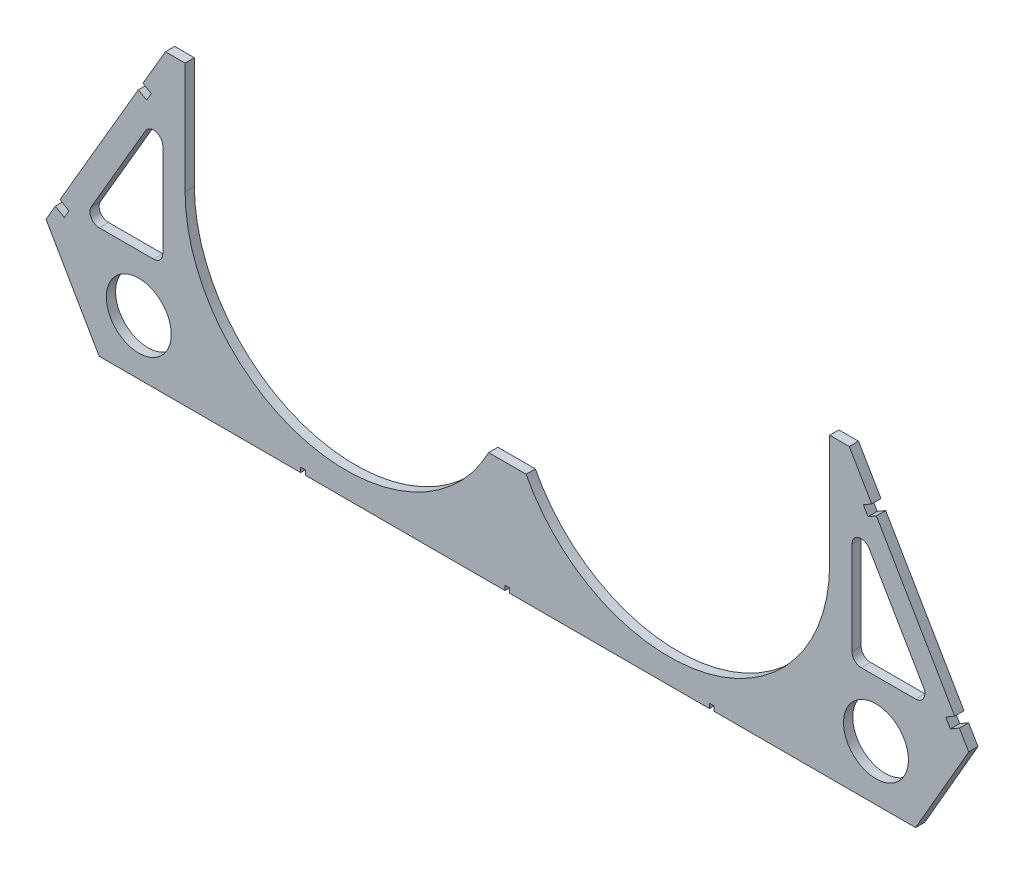
SolidWorks part; units mm, degrees
material "Balsa"
ref_plane "Front Plane" through (0, 0, 0) normal (0, 0, 1) x (1, 0, 0)
ref_plane "Top Plane" through (0, 0, 0) normal (0, 1, 0) x (1, 0, 0)
ref_plane "Right Plane" through (0, 0, 0) normal (1, 0, 0) x (0, 0, -1)
sketch "Sketch1" plane through (0, 0, 0) normal (0, 0, 1) x (1, 0, 0)
  line L1 (279.4, 0) -> (315.7855, 63.0215)
  line L3 (0, 0) -> (0, 203.2) construction
  line L5 (-234.0358, 203.2) -> (-315.7855, 63.0215)
  line L11 (279.4, 0) -> (-279.4, 0)
  line L14 (-234.0358, 203.2) -> (234.0358, 203.2)
  line L15 (234.0358, 203.2) -> (315.7855, 63.0215)
  line L16 (0, -796.8) -> (0, 49203.2) construction
  line L17 (-279.4, 0) -> (-315.7855, 63.0215)
  point P6 (114.3, 190.1315)
  point P12 (-114.3, 190.1315)
  dimension "D1" = 279.4
  dimension "D2" = 72.771
  dimension "D3" = 59.75
  dimension "D4" = 203.2
  dimension "D5" = 120
extrude "Boss-Extrude1" add sketch "Sketch1" along normal blind 6.35
sketch "Sketch4" plane through (0, 0, 6.35) normal (0, 0, 1) x (1, 0, 0)
  line L1 (-279.4, 0) -> (279.4, 0) construction
  line L3 (0, 203.2) -> (0, -21.9147) construction
  line L4 (234.0358, 203.2) -> (-234.0358, 203.2) construction
  circle A0 centre (110.49, 127) radius 110.109
  circle A1 centre (-110.49, 127) radius 110.109
  dimension "D1" = 220.218
  dimension "D3" = 127
  dimension "D2" = 220.98
extrude "Cut-Extrude3" cut sketch "Sketch4" against normal up to next
sketch "Sketch7" [suppressed] plane through (0, 0, 6.35) normal (0, 0, 1) x (1, 0, 0)
  line L0 (-279.4, 0) -> (279.4, 0) construction
  line L1 (0, -1000) -> (0, 49000) construction
  line L2 (-279.4, 0) -> (279.4, 0) construction
  circle A0 centre (110.49, 127) radius 110.109
  circle A1 centre (-110.49, 127) radius 110.109
  point P10 (0, 0)
  dimension "D1" = 220.218
  dimension "D3" = 127
  dimension "D2" = 220.98
extrude "Cut-Extrude6" [suppressed] cut sketch "Sketch7" against normal up to next
sketch "Sketch8" [suppressed] plane through (0, 0, 6.35) normal (0, 0, 1) x (1, 0, 0)
  line L0 (0, -1000) -> (0, 49000) construction
  line L1 (-279.4, 0) -> (279.4, 0) construction
  line L2 (-279.4, 0) -> (279.4, 0) construction
  circle A0 centre (252.4061, 31.75) radius 15.875
  circle A1 centre (-252.4061, 31.75) radius 15.875
  point P11 (0, 0)
  dimension "D1" = 31.75
  dimension "D2" = 63.5
  dimension "D3" = 31.75
extrude "Cut-Extrude7" [suppressed] cut sketch "Sketch8" against normal through all
sketch "Sketch9" plane through (0, 0, 6.35) normal (0, 0, 1) x (1, 0, 0)
  line L2 (0, -1000) -> (0, 49000) construction
  line L3 (-279.4, 0) -> (279.4, 0) construction
  circle A0 centre (252.2855, 37.6215) radius 22.225
  circle A1 centre (-252.2855, 37.6215) radius 22.225
  point P9 (0, 0)
  dimension "D1" = 44.45
  dimension "D2" = 25.4
  dimension "D3" = 63.5
extrude "Cut-Extrude8" cut sketch "Sketch9" against normal through all
sketch "Sketch10" [suppressed] plane through (0, 0, 6.35) normal (0, 0, 1) x (1, 0, 0)
  line L0 (-279.4, 0) -> (279.4, 0) construction
  line L1 (118.618, 0) -> (141.478, 0)
  line L2 (118.618, 0) -> (118.618, 3.175)
  line L3 (118.618, 3.175) -> (141.478, 3.175)
  line L4 (141.478, 0) -> (141.478, 3.175)
  line L5 (-279.4, 0) -> (279.4, 0) construction
  line L6 (-1.5875, 0) -> (1.5875, 0)
  line L11 (-1.5875, 0) -> (-1.5875, 3.175)
  line L12 (-1.5875, 3.175) -> (1.5875, 3.175)
  line L13 (1.5875, 0) -> (1.5875, 3.175)
  line L14 (0, -1000) -> (0, 49000) construction
  line L15 (-141.478, 0) -> (-141.478, 3.175)
  line L16 (-118.618, 3.175) -> (-141.478, 3.175)
  line L17 (-118.618, 0) -> (-118.618, 3.175)
  line L18 (-118.618, 0) -> (-141.478, 0)
  point P13 (0, 0)
  dimension "D1" = 22.86
  dimension "D2" = 3.175
  dimension "D3" = 137.922
  dimension "D4" = 3.175
  dimension "D5" = 3.175
  dimension "D6" = 279.4
extrude "Cut-Extrude9" [suppressed] cut sketch "Sketch10" against normal through all
sketch "Sketch11" plane through (0, 0, 6.35) normal (0, 0, 1) x (1, 0, 0)
  line L0 (-279.4, 0) -> (279.4, 0) construction
  line L1 (141.478, 0) -> (138.303, 0)
  line L2 (141.478, 0) -> (141.478, 3.175)
  line L3 (141.478, 3.175) -> (138.303, 3.175)
  line L4 (138.303, 0) -> (138.303, 3.175)
  line L10 (1.5875, 3.175) -> (-1.5875, 3.175)
  line L11 (-1.5875, 0) -> (-1.5875, 3.175)
  line L12 (1.5875, 0) -> (-1.5875, 0)
  line L13 (1.5875, 0) -> (1.5875, 3.175)
  line L14 (-138.303, 3.175) -> (-141.478, 3.175)
  line L15 (-141.478, 0) -> (-141.478, 3.175)
  line L16 (-138.303, 0) -> (-141.478, 0)
  line L17 (-138.303, 0) -> (-138.303, 3.175)
  line L18 (-279.4, 0) -> (279.4, 0) construction
  point P6 (0, 0)
  point P9 (0, 0)
  dimension "D1" = 0
  dimension "D2" = 3.175
  dimension "D3" = 3.175
  dimension "D4" = 137.922
  dimension "D5" = 3
extrude "Cut-Extrude10" cut sketch "Sketch11" against normal through all
sketch "Sketch13" plane through (0, 0, 6.35) normal (0, 0, 1) x (1, 0, 0)
  line L0 (-37.5175, 76.2) -> (35.6442, 76.2)
  line L5 (-220.599, 127) -> (-220.599, 203.2)
  line L6 (-189.973, 203.2) -> (-234.0358, 203.2) construction
  line L7 (220.599, 127) -> (220.599, 203.2)
  line L9 (234.0358, 203.2) -> (189.973, 203.2) construction
  line L10 (220.599, 203.2) -> (-220.599, 203.2)
  line L11 (-37.5175, 76.2) -> (-220.599, 127)
  line L12 (35.6442, 76.2) -> (220.599, 127)
  arc A0 (-189.973, 203.2) -> (-31.007, 203.2) centre (-110.49, 127) ccw construction
  arc A2 (31.007, 203.2) -> (189.973, 203.2) centre (110.49, 127) ccw construction
  arc A3 (31.007, 203.2) -> (189.973, 203.2) centre (110.49, 127) ccw construction
extrude "Cut-Extrude12" cut sketch "Sketch13" against normal through all
sketch "Sketch16" plane through (0, 0, 0) normal (0, 0, -1) x (-1, 0, 0)
  line L0 (-247.6744, 149.562) -> (-284.889, 85.749)
  line L1 (-235.839, 146.363) -> (-235.839, 82.55)
  line L2 (-242.189, 76.2) -> (-279.4037, 76.2)
  line L3 (-141.478, 0) -> (-279.4, 0) construction
  line L4 (-220.599, 127) -> (-220.599, 203.2) construction
  line L5 (-315.7855, 63.0215) -> (-234.0358, 203.2) construction
  line L6 (0, -923.8) -> (0, 49076.2) construction
  line L7 (12.7999, 76.2) -> (-12.7999, 76.2) construction
  line L8 (242.189, 76.2) -> (279.4037, 76.2)
  line L9 (235.839, 146.363) -> (235.839, 82.55)
  line L10 (247.6744, 149.562) -> (284.889, 85.749)
  arc A0 (-247.6744, 149.562) -> (-235.839, 146.363) centre (-242.189, 146.363) cw
  arc A1 (-235.839, 82.55) -> (-242.189, 76.2) centre (-242.189, 82.55) cw
  arc A2 (-284.889, 85.749) -> (-279.4037, 76.2) centre (-279.4037, 82.55) ccw
  arc A3 (284.889, 85.749) -> (279.4037, 76.2) centre (279.4037, 82.55) cw
  arc A4 (235.839, 82.55) -> (242.189, 76.2) centre (242.189, 82.55) ccw
  arc A5 (247.6744, 149.562) -> (235.839, 146.363) centre (242.189, 146.363) ccw
  point P20 (0, 76.2)
  dimension "D4" = 6.35
  dimension "D1" = 15.24
  dimension "D2" = 15.24
  dimension "D3" = 76.2
extrude "Cut-Extrude15" cut sketch "Sketch16" against normal through all
sketch "Sketch18" plane through (0, 0, 0) normal (0, 0, -1) x (-1, 0, 0)
  line L0 (-247.6744, 149.562) -> (-284.889, 85.749)
  line L1 (-279.4037, 76.2) -> (-242.189, 76.2)
  line L2 (-235.839, 82.55) -> (-235.839, 146.363)
  line L3 (-220.599, 203.2) -> (-220.599, 127) construction
  line L4 (-315.7855, 63.0215) -> (-234.0358, 203.2) construction
  line L5 (0, -923.8) -> (0, 49076.2) construction
  line L6 (-12.7999, 76.2) -> (12.7999, 76.2) construction
  line L7 (-141.478, 0) -> (-279.4, 0) construction
  line L8 (235.839, 82.55) -> (235.839, 146.363)
  line L9 (279.4037, 76.2) -> (242.189, 76.2)
  line L10 (247.6744, 149.562) -> (284.889, 85.749)
  arc A0 (-235.839, 146.363) -> (-247.6744, 149.562) centre (-242.189, 146.363) ccw
  arc A1 (-242.189, 76.2) -> (-235.839, 82.55) centre (-242.189, 82.55) ccw
  arc A2 (-284.889, 85.749) -> (-279.4037, 76.2) centre (-279.4037, 82.55) ccw
  arc A3 (284.889, 85.749) -> (279.4037, 76.2) centre (279.4037, 82.55) cw
  arc A4 (242.189, 76.2) -> (235.839, 82.55) centre (242.189, 82.55) cw
  arc A5 (235.839, 146.363) -> (247.6744, 149.562) centre (242.189, 146.363) cw
  point P21 (0, 76.2)
  dimension "D4" = 6.35
  dimension "D1" = 15.24
  dimension "D2" = 15.24
  dimension "D3" = 76.2
extrude "Cut-Extrude17" [suppressed] cut sketch "Sketch18" against normal through all
sketch "Sketch19" plane through (0, 0, 0) normal (0, 0, -1) x (-1, 0, 0)
  line L1 (0, -923.8) -> (0, 49076.2) construction
  line L5 (-306.1886, 79.4776) -> (-309.3876, 73.9922)
  line L6 (-315.7855, 63.0215) -> (-234.0358, 203.2) construction
  line L7 (-309.3876, 73.9922) -> (-303.244, 70.4094)
  line L8 (-303.244, 70.4094) -> (-300.045, 75.8948)
  line L9 (-300.045, 75.8948) -> (-306.1886, 79.4776)
  line L10 (-253.0148, 171.6328) -> (-246.8712, 168.0499)
  line L11 (-246.8712, 168.0499) -> (-243.6722, 173.5353)
  line L12 (-243.6722, 173.5353) -> (-249.8158, 177.1181)
  line L13 (-249.8158, 177.1181) -> (-253.0148, 171.6328)
  line L15 (-12.7999, 76.2) -> (12.7999, 76.2) construction
  line L24 (249.8158, 177.1181) -> (253.0148, 171.6328)
  line L25 (243.6722, 173.5353) -> (249.8158, 177.1181)
  line L26 (246.8712, 168.0499) -> (243.6722, 173.5353)
  line L27 (253.0148, 171.6328) -> (246.8712, 168.0499)
  line L28 (300.045, 75.8948) -> (306.1886, 79.4776)
  line L29 (303.244, 70.4094) -> (300.045, 75.8948)
  line L30 (309.3876, 73.9922) -> (303.244, 70.4094)
  line L31 (306.1886, 79.4776) -> (309.3876, 73.9922)
  point P19 (0, 76.2)
  dimension "D1" = 6.35
  dimension "D2" = 7.112
  dimension "D3" = 12.7
  dimension "D5" = 30.48
  dimension "D4" = 2
extrude "Cut-Extrude18" cut sketch "Sketch19" against normal through all
